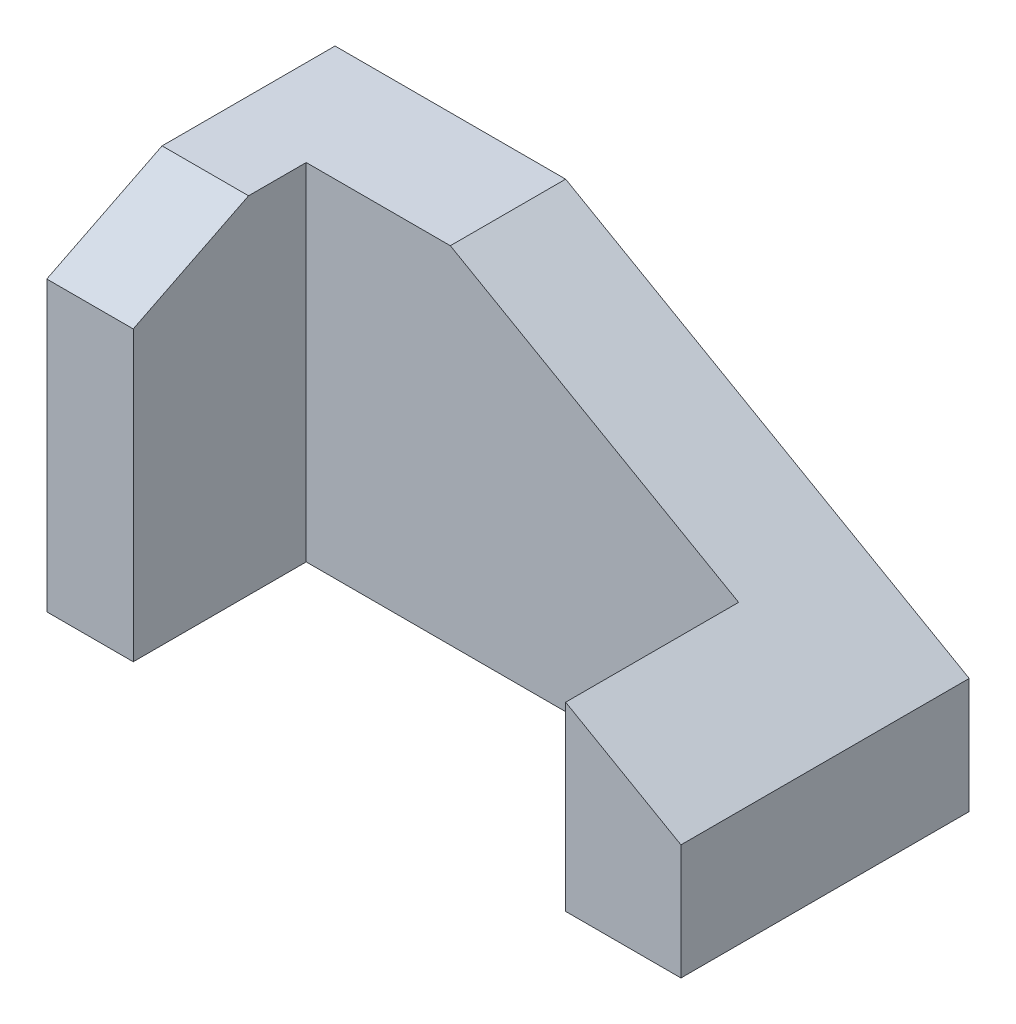
SolidWorks part; units mm, degrees
ref_plane "정면" through (0, 0, 0) normal (0, 0, 1) x (1, 0, 0)
ref_plane "윗면" through (0, 0, 0) normal (0, 1, 0) x (1, 0, 0)
ref_plane "우측면" through (0, 0, 0) normal (1, 0, 0) x (0, 0, -1)
sketch "스케치1" plane through (0, 0, 0) normal (0, 1, 0) x (1, 0, 0)
  line L1 (0, 0) -> (110, 0)
  line L2 (0, 0) -> (0, 50)
  line L3 (0, 50) -> (110, 50)
  line L4 (110, 0) -> (110, 50)
  dimension "D1" = 50
  dimension "D2" = 110
extrude "보스-돌출1" add sketch "스케치1" along normal blind 60
sketch "스케치2" plane through (0, 60, 0) normal (0, 1, 0) x (1, 0, 0)
  line L1 (15, 0) -> (90, 0)
  line L2 (15, 0) -> (15, 30)
  line L3 (15, 30) -> (90, 30)
  line L4 (90, 0) -> (90, 30)
  dimension "D1" = 30
  dimension "D2" = 15
  dimension "D3" = 20
extrude "컷-돌출1" cut sketch "스케치2" against normal through all
sketch "스케치4" plane through (0, 0, 0) normal (0, 0, 1) x (1, 0, 0)
  line L0 (40, 60) -> (110, 20)
  line L1 (90, 60) -> (15, 60) construction
  line L2 (110, 60) -> (110, 0) construction
  dimension "D1" = 20
  dimension "D2" = 40
extrude "컷-돌출2" cut sketch "스케치4" against normal through all and the other way through all
sketch "스케치5" plane through (15, 0, 0) normal (1, 0, 0) x (0, 0, -1)
  line L0 (20, 60) -> (0, 50)
  line L1 (30, 60) -> (0, 60) construction
  line L2 (0, 0) -> (0, 60) construction
  dimension "D1" = 10
  dimension "D2" = 30
extrude "컷-돌출3" cut sketch "스케치5" against normal through all and the other way through all flip side to cut
